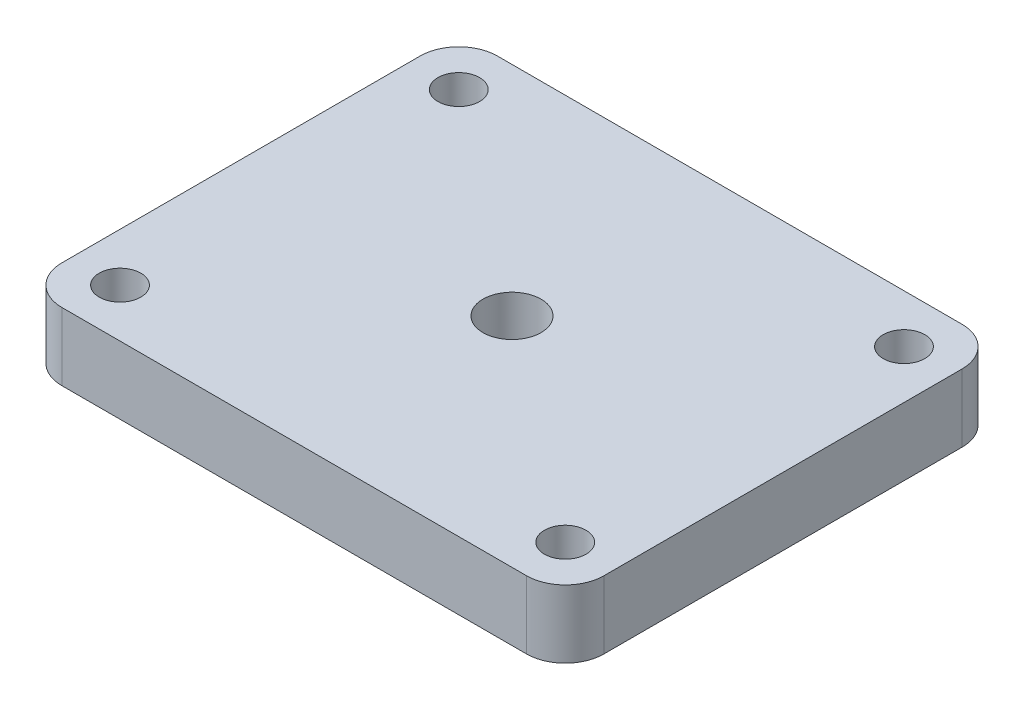
SolidWorks part; units mm, degrees
ref_plane "前视基准面" through (0, 0, 0) normal (0, 0, 1) x (1, 0, 0)
ref_plane "上视基准面" through (0, 0, 0) normal (0, 1, 0) x (1, 0, 0)
ref_plane "右视基准面" through (0, 0, 0) normal (1, 0, 0) x (0, 0, -1)
sketch "草图1" plane through (0, 0, 0) normal (0, 1, 0) x (1, 0, 0)
  line L1 (-24, -22.5) -> (24, -22.5)
  line L2 (-28, -18.5) -> (-28, 18.5)
  line L3 (-24, 22.5) -> (24, 22.5)
  line L4 (28, -18.5) -> (28, 18.5)
  line L5 (-28, -22.5) -> (28, 22.5) construction
  line L6 (-28, 22.5) -> (28, -22.5) construction
  line L7 (-23, 17.5) -> (23, 17.5)
  line L8 (-23, 17.5) -> (-23, -17.5)
  line L9 (-23, -17.5) -> (23, -17.5)
  line L10 (23, 17.5) -> (23, -17.5)
  line L11 (-23, 17.5) -> (23, -17.5) construction
  line L12 (-23, -17.5) -> (23, 17.5) construction
  circle A0 centre (-23, 17.5) radius 2.15
  circle A1 centre (-23, -17.5) radius 2.15
  circle A2 centre (23, -17.5) radius 2.15
  circle A3 centre (23, 17.5) radius 2.15
  arc A4 (-28, 18.5) -> (-24, 22.5) centre (-24, 18.5) cw
  arc A5 (-24, -22.5) -> (-28, -18.5) centre (-24, -18.5) cw
  arc A6 (24, -22.5) -> (28, -18.5) centre (24, -18.5) ccw
  arc A7 (24, 22.5) -> (28, 18.5) centre (24, 18.5) cw
  circle A8 centre (0, 0) radius 3
  point P0 (0, 0)
  point P6 (0, 0)
  dimension "D3" = 4.3
  dimension "D4" = 4.3
  dimension "D5" = 4.3
  dimension "D6" = 4.3
  dimension "D9" = 4
  dimension "D10" = 6
  dimension "D1" = 46
  dimension "D2" = 35
  dimension "D7" = 56
  dimension "D8" = 45
extrude "凸台-拉伸1" add sketch "草图1" along normal blind 1 contours A7 L3 A4 L2 A5 L1 A6 L4 A3 L10 A2 L9 A1 L8 A0 L7 | A3 L7 A0 L8 A1 L9 A2 L10
sketch "草图13" plane through (0, 0, 0) normal (0, -1, 0) x (1, 0, 0)
  line L0 (-24, -22.5) -> (24, -22.5) construction
  line L1 (-28, 18.5) -> (-28, -18.5) construction
  line L2 (-24, 22.5) -> (24, 22.5) construction
  line L3 (28, 18.5) -> (28, -18.5) construction
  line L4 (-24, -22.5) -> (24, -22.5)
  line L5 (-28, 18.5) -> (-28, -18.5)
  line L6 (-24, 22.5) -> (24, 22.5)
  line L7 (28, 18.5) -> (28, -18.5)
  arc A0 (-28, -18.5) -> (-24, -22.5) centre (-24, -18.5) ccw construction
  arc A1 (-24, 22.5) -> (-28, 18.5) centre (-24, 18.5) ccw construction
  circle A2 centre (-23, 17.5) radius 2.15 construction
  circle A3 centre (-23, -17.5) radius 2.15 construction
  circle A4 centre (23, -17.5) radius 2.15 construction
  circle A5 centre (23, 17.5) radius 2.15 construction
  arc A6 (28, 18.5) -> (24, 22.5) centre (24, 18.5) ccw construction
  arc A7 (24, -22.5) -> (28, -18.5) centre (24, -18.5) ccw construction
  arc A8 (-28, -18.5) -> (-24, -22.5) centre (-24, -18.5) ccw
  arc A9 (-24, 22.5) -> (-28, 18.5) centre (-24, 18.5) ccw
  circle A10 centre (-23, 17.5) radius 2.15
  circle A11 centre (-23, -17.5) radius 2.15
  circle A12 centre (23, -17.5) radius 2.15
  circle A13 centre (23, 17.5) radius 2.15
  arc A14 (28, 18.5) -> (24, 22.5) centre (24, 18.5) ccw
  arc A15 (24, -22.5) -> (28, -18.5) centre (24, -18.5) ccw
  circle A16 centre (0, 0) radius 3 construction
  circle A17 centre (0, 0) radius 3
extrude "凸台-拉伸5" add sketch "草图13" along normal blind 6
sketch3d "URDF Reference"
  line L0 (0, 0, 0) -> (10, 0, 0) construction
  line L1 (0, 0, 0) -> (0, 0, -10) construction
  point P0 (0, 0, 0)
